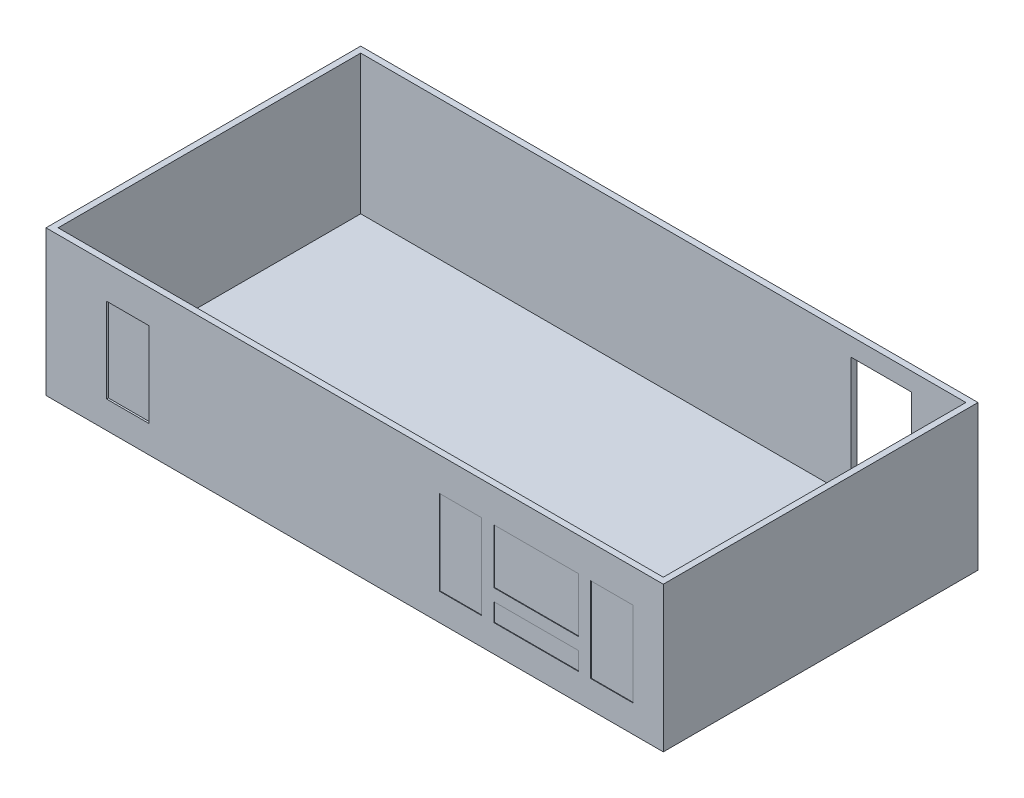
SolidWorks part; units mm, degrees
ref_plane "Front Plane" through (0, 0, 0) normal (0, 0, 1) x (1, 0, 0)
ref_plane "Top Plane" through (0, 0, 0) normal (0, 1, 0) x (1, 0, 0)
ref_plane "Right Plane" through (0, 0, 0) normal (1, 0, 0) x (0, 0, -1)
sketch "Sketch1" plane through (0, 0, 0) normal (0, 1, 0) x (1, 0, 0)
  line L0 (0, 0) -> (-10000, 0)
  line L1 (-10000, 0) -> (-10000, 5000)
  line L2 (-10000, 5000) -> (0, 5000)
  line L3 (0, 5000) -> (0, 0)
  line L4 (-10100, 5100) -> (100, 5100)
  line L5 (100, 5100) -> (100, -100)
  line L6 (100, -100) -> (-10100, -100)
  line L7 (-10100, -100) -> (-10100, 5100)
  dimension "D1" = 10000
  dimension "D2" = 5000
  dimension "D3" = 100
extrude "Boss-Extrude1" add sketch "Sketch1" along normal blind 2300
sketch "Sketch2" plane through (0, 0, 0) normal (0, 1, 0) x (1, 0, 0)
  line L0 (-10100, 5100) -> (-10100, -100)
  line L1 (-10100, -100) -> (100, -100)
  line L2 (100, -100) -> (100, 5100)
  line L3 (100, 5100) -> (-10100, 5100)
extrude "Boss-Extrude2" add sketch "Sketch2" against normal blind 100
sketch "Sketch3" plane through (0, 0, 100) normal (0, 0, 1) x (1, 0, 0)
  line L0 (-400, 1750) -> (-400, 350)
  line L1 (-400, 350) -> (-1100, 350)
  line L2 (-1100, 350) -> (-1100, 1750)
  line L3 (-1100, 1750) -> (-400, 1750)
  line L4 (-1300, 1750) -> (-1300, 850)
  line L5 (-1300, 850) -> (-2700, 850)
  line L6 (-2700, 850) -> (-2700, 1750)
  line L7 (-2700, 1750) -> (-1300, 1750)
  line L8 (-1300, 650) -> (-1300, 350)
  line L9 (-1300, 350) -> (-2700, 350)
  line L10 (-2700, 350) -> (-2700, 650)
  line L11 (-2700, 650) -> (-1300, 650)
  line L12 (-2900, 350) -> (-2900, 1750)
  line L13 (-2900, 1750) -> (-3600, 1750)
  line L14 (-3600, 1750) -> (-3600, 350)
  line L15 (-3600, 350) -> (-2900, 350)
  line L16 (100, 2300) -> (100, -100) construction
  line L17 (-10100, 2300) -> (100, 2300) construction
  dimension "D1" = 500
  dimension "D2" = 200
  dimension "D3" = 700
  dimension "D4" = 1400
  dimension "D5" = 1400
  dimension "D6" = 1400
  dimension "D7" = 300
  dimension "D8" = 200
  dimension "D9" = 200
  dimension "D10" = 700
  dimension "D11" = 1400
  dimension "D12" = 550
extrude "Cut-Extrude1" cut sketch "Sketch3" against normal up to next
ref_plane "Plane1" through (0, 0, 70) normal (0, 0, 1) x (1, 0, 0)
sketch "Sketch5" plane through (0, 0, 70) normal (0, 0, 1) x (1, 0, 0)
  line L0 (-3600, 1750) -> (-2900, 1750)
  line L1 (-2900, 1750) -> (-2900, 350)
  line L2 (-2900, 350) -> (-3600, 350)
  line L3 (-3600, 350) -> (-3600, 1750)
  line L4 (-2700, 1750) -> (-1300, 1750)
  line L5 (-1300, 1750) -> (-1300, 850)
  line L6 (-1300, 850) -> (-2700, 850)
  line L7 (-2700, 850) -> (-2700, 1750)
  line L8 (-2700, 350) -> (-2700, 650)
  line L9 (-2700, 650) -> (-1300, 650)
  line L10 (-1300, 650) -> (-1300, 350)
  line L11 (-1300, 350) -> (-2700, 350)
  line L12 (-1100, 350) -> (-400, 350)
  line L13 (-400, 350) -> (-400, 1750)
  line L14 (-400, 1750) -> (-1100, 1750)
  line L15 (-1100, 1750) -> (-1100, 350)
extrude "Boss-Extrude5" add sketch "Sketch5" along normal blind 20
sketch "Sketch6" plane through (0, 0, 100) normal (0, 0, 1) x (1, 0, 0)
  line L0 (-9100, 1750) -> (-9100, 350)
  line L1 (-9100, 350) -> (-8400, 350)
  line L2 (-8400, 350) -> (-8400, 1750)
  line L3 (-8400, 1750) -> (-9100, 1750)
  line L4 (-10100, 2300) -> (-10100, -100) construction
  line L5 (-10100, -100) -> (100, -100) construction
  dimension "D1" = 700
  dimension "D2" = 1400
  dimension "D3" = 1000
  dimension "D4" = 450
extrude "Cut-Extrude2" cut sketch "Sketch6" against normal up to next
sketch "Sketch7" plane through (0, 0, 70) normal (0, 0, 1) x (1, 0, 0)
  line L0 (-9100, 1750) -> (-8400, 1750)
  line L1 (-8400, 1750) -> (-8400, 350)
  line L2 (-8400, 350) -> (-9100, 350)
  line L3 (-9100, 350) -> (-9100, 1750)
extrude "Boss-Extrude6" add sketch "Sketch7" against normal blind 20
sketch "Sketch8" plane through (0, 0, -5100) normal (0, 0, -1) x (-1, 0, 0)
  line L0 (900, 2000) -> (900, 0)
  line L1 (900, 0) -> (1900, 0)
  line L2 (1900, 0) -> (1900, 2000)
  line L3 (1900, 2000) -> (900, 2000)
  line L4 (-100, -100) -> (10100, -100) construction
  line L5 (-100, 2300) -> (-100, -100) construction
  dimension "D1" = 2000
  dimension "D2" = 1000
  dimension "D3" = 100
  dimension "D4" = 1000
extrude "Cut-Extrude3" cut sketch "Sketch8" against normal up to next
